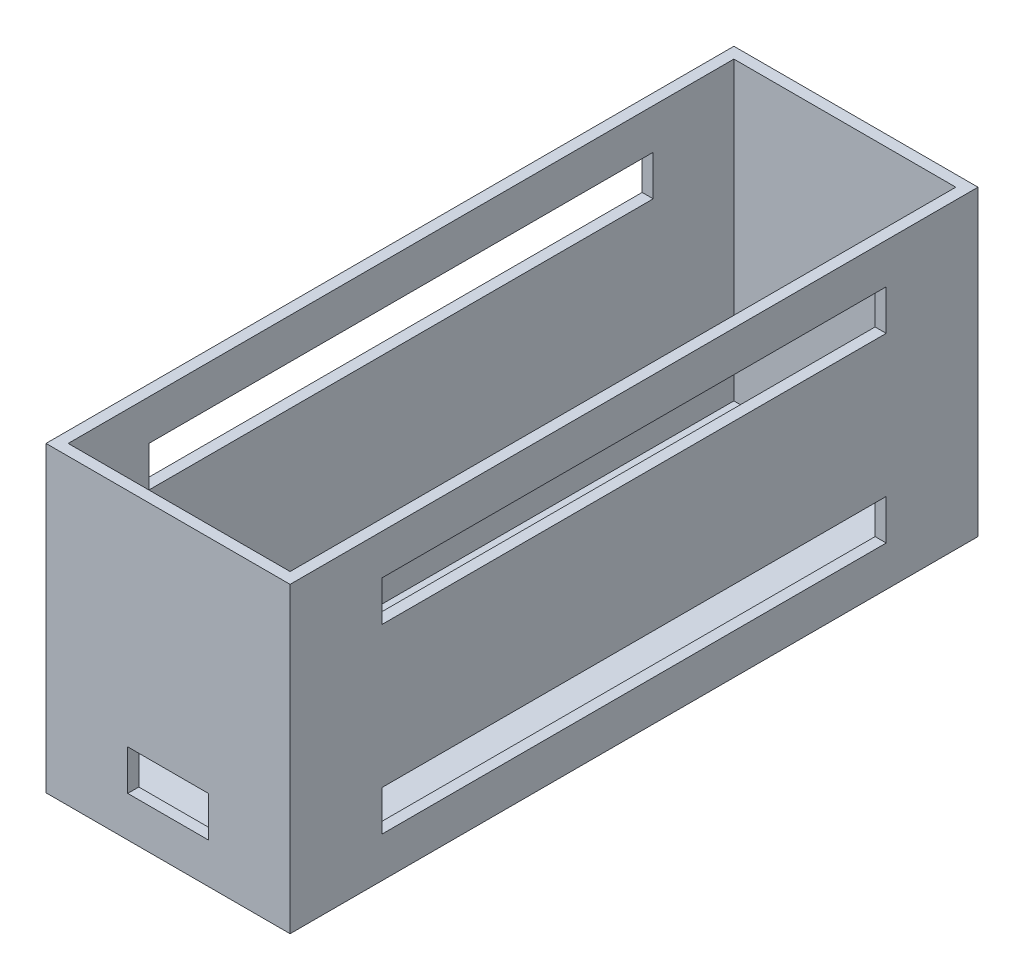
SolidWorks part; units mm, degrees
ref_plane "Front Plane" through (0, 0, 0) normal (0, 0, 1) x (1, 0, 0)
ref_plane "Top Plane" through (0, 0, 0) normal (0, 1, 0) x (1, 0, 0)
ref_plane "Right Plane" through (0, 0, 0) normal (1, 0, 0) x (0, 0, -1)
sketch "Sketch1" plane through (0, 0, 0) normal (0, 0, 1) x (1, 0, 0)
  line L1 (30.25, -37.5) -> (-30.25, -37.5)
  line L2 (30.25, -37.5) -> (30.25, 37.5)
  line L3 (30.25, 37.5) -> (-30.25, 37.5)
  line L4 (-30.25, -37.5) -> (-30.25, 37.5)
  line L5 (30.25, -37.5) -> (-30.25, 37.5) construction
  line L6 (30.25, 37.5) -> (-30.25, -37.5) construction
  point P0 (0, 0)
  dimension "D1" = 60.5
  dimension "D2" = 75
extrude "Boss-Extrude1" add sketch "Sketch1" along normal mid plane 170.5
sketch "Sketch2" plane through (0, 37.5, 0) normal (0, 1, 0) x (1, 0, 0)
  line L1 (27.5, -82.5) -> (-27.5, -82.5)
  line L2 (27.5, -82.5) -> (27.5, 82.5)
  line L3 (27.5, 82.5) -> (-27.5, 82.5)
  line L4 (-27.5, -82.5) -> (-27.5, 82.5)
  line L5 (27.5, -82.5) -> (-27.5, 82.5) construction
  line L6 (27.5, 82.5) -> (-27.5, -82.5) construction
  point P0 (0, 0)
  dimension "D1" = 55
  dimension "D2" = 165
extrude "Cut-Extrude1" cut sketch "Sketch2" against normal blind 73.375
sketch "Sketch3" plane through (0, 0, 85.25) normal (0, 0, 1) x (1, 0, 0)
  line L0 (-30.25, -37.5) -> (30.25, -37.5) construction
  line L1 (10, -27.5) -> (-10, -27.5)
  line L2 (10, -27.5) -> (10, -17.5)
  line L3 (10, -17.5) -> (-10, -17.5)
  line L4 (-10, -27.5) -> (-10, -17.5)
  line L5 (10, -27.5) -> (-10, -17.5) construction
  line L6 (10, -17.5) -> (-10, -27.5) construction
  line L7 (0, 0) -> (0, -37.5) construction
  point P0 (0, -22.5)
  dimension "D1" = 10
  dimension "D2" = 20
  dimension "D3" = 10
extrude "Cut-Extrude2" cut sketch "Sketch3" against normal up to surface (2.75 mm away) up to face at (0, 0.8125, 82.5)
sketch "Sketch7" plane through (-30.25, 0, 0) normal (-1, 0, 0) x (0, 0, 1)
  line L0 (-85.25, 37.5) -> (-85.25, -37.5) construction
  line L1 (62.5, -27.5) -> (-62.5, -27.5)
  line L2 (62.5, -27.5) -> (62.5, -17.5)
  line L3 (62.5, -17.5) -> (-62.5, -17.5)
  line L4 (-62.5, -27.5) -> (-62.5, -17.5)
  line L5 (62.5, -27.5) -> (-62.5, -17.5) construction
  line L6 (62.5, -17.5) -> (-62.5, -27.5) construction
  line L8 (85.25, 37.5) -> (85.25, -37.5) construction
  line L9 (85.25, -37.5) -> (-85.25, -37.5) construction
  line L10 (-85.25, 0) -> (85.25, 0) construction
  line L11 (62.5, 17.5) -> (-62.5, 17.5)
  line L12 (-62.5, 27.5) -> (-62.5, 17.5)
  line L13 (62.5, 27.5) -> (-62.5, 27.5)
  line L14 (62.5, 27.5) -> (62.5, 17.5)
  point P0 (0, -22.5)
  dimension "D1" = 22.75
  dimension "D2" = 22.75
  dimension "D3" = 10
  dimension "D4" = 10
extrude "Cut-Extrude4" cut sketch "Sketch7" against normal through all contours L11 L12 L13 L14 | L2 L1 L4 L3
fillet "Fillet1" [suppressed] radius 10
